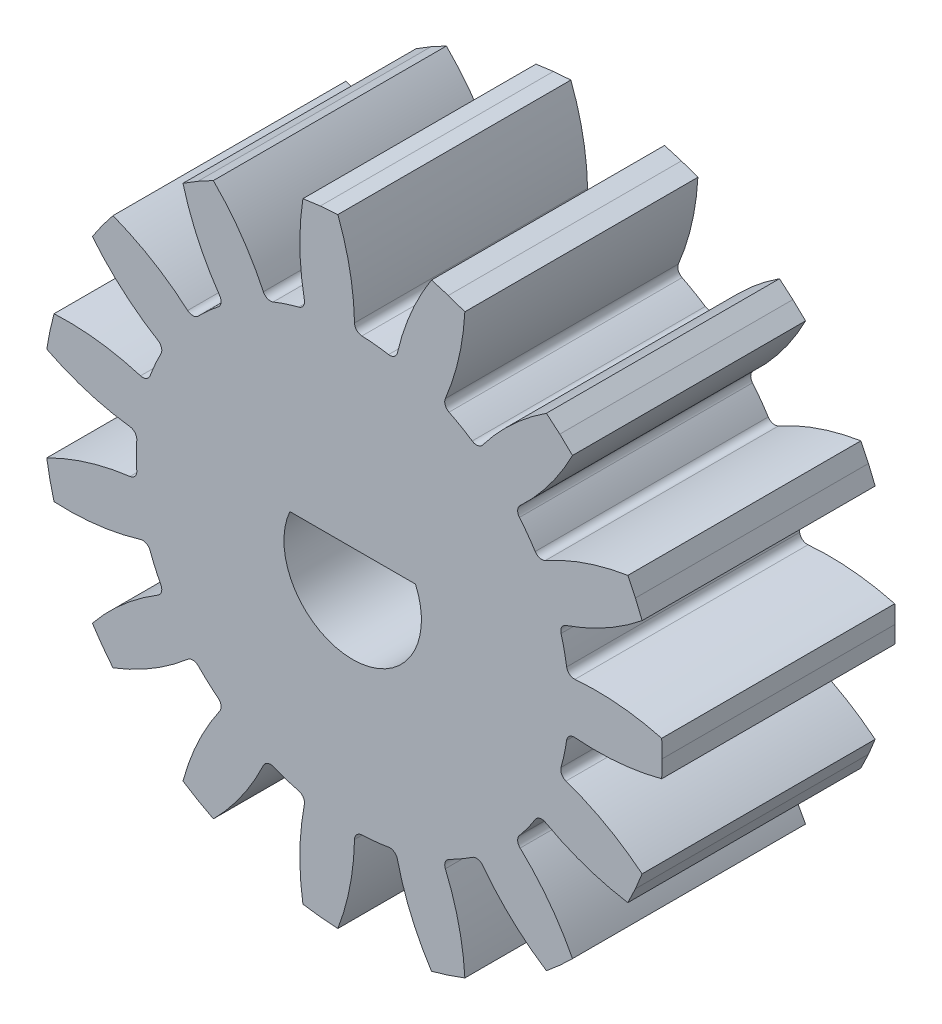
SolidWorks part; units mm, degrees
ref_plane "Front Plane" through (0, 0, 0) normal (0, 0, 1) x (1, 0, 0)
ref_plane "Top Plane" through (0, 0, 0) normal (0, 1, 0) x (1, 0, 0)
ref_plane "Right Plane" through (0, 0, 0) normal (1, 0, 0) x (0, 0, -1)
sketch "Sketch1" plane through (0, 0, 0) normal (0, 0, 1) x (1, 0, 0)
  line L0 (0, 0) -> (74.4139, 0) construction
  line L1 (0, 0) -> (9.0784, 1.9297) construction
  line L2 (0, 0) -> (74.4139, 8.4784) construction
  line L3 (0, 0) -> (74.4139, 4.2255) construction
  line L4 (13.2599, 0.753) -> (13.2812, 0)
  line L5 (0, 0) -> (9.0784, -1.9297) construction
  line L6 (0, 0) -> (9.0784, 1.9297)
  line L7 (0, 0) -> (9.0784, -1.9297) construction
  line L8 (0, 0) -> (9.0784, -1.9297)
  line L9 (13.2599, -0.753) -> (13.2812, 0)
  circle A0 centre (0, 0) radius 13.2812 construction
  circle A1 centre (0, 0) radius 11.7188 construction
  circle A2 centre (0, 0) radius 9.2812 construction
  arc A3 (9.2216, 1.0507) -> (13.2599, 0.753) centre (10.4542, -9.7675) cw
  arc A4 (9.2216, 1.0507) -> (9.0784, 1.9297) centre (0, 0) ccw
  arc A5 (9.2216, -1.0507) -> (9.0784, -1.9297) centre (0, 0) cw
  arc A6 (9.2216, -1.0507) -> (13.2599, -0.753) centre (10.4542, 9.7675) ccw
  dimension "D1" = 26.5625
  dimension "D2" = 1.5625
  dimension "D3" = 2.4375
  dimension "D4" = 12
  dimension "D5" = 6.5
  dimension "D6" = 3.25
extrude "Boss-Extrude1" add sketch "Sketch1" along normal blind 10
fillet "Fillet1" radius 0.3325 2 edges at (9.2216, 1.0507, 5) (9.2216, -1.0507, 5)
pattern_circular "CirPattern1" count 15 over 360 about axis through (0, 0, 0) along (0, 0, 1) of "Boss-Extrude1", "Fillet1"
sketch "Sketch2" plane through (0, 0, 0) normal (0, 0, -1) x (-1, 0, 0)
  line L0 (-2.6949, 1.2) -> (2.6949, 1.2)
  arc A0 (-2.6949, 1.2) -> (2.6949, 1.2) centre (0, 0) ccw
  dimension "D1" = 5.9
  dimension "D2" = 1.2
extrude "Cut-Extrude1" cut sketch "Sketch2" against normal up to next
